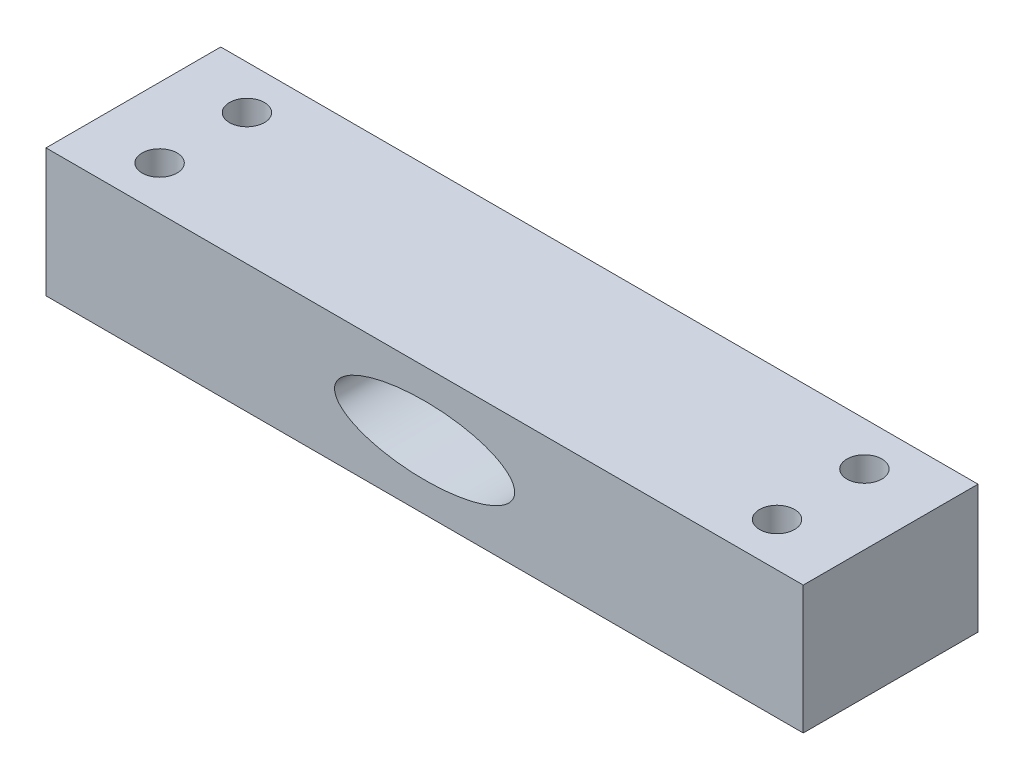
SolidWorks part; units mm, degrees
ref_plane "Front Plane" through (0, 0, 0) normal (0, 0, 1) x (1, 0, 0)
ref_plane "Top Plane" through (0, 0, 0) normal (0, 1, 0) x (1, 0, 0)
ref_plane "Right Plane" through (0, 0, 0) normal (1, 0, 0) x (0, 0, -1)
sketch "Sketch1" plane through (0, 0, 0) normal (0, 1, 0) x (1, 0, 0)
  line L1 (-65, -15) -> (65, -15)
  line L2 (-65, -15) -> (-65, 15)
  line L3 (-65, 15) -> (65, 15)
  line L4 (65, -15) -> (65, 15)
  line L5 (0, 15) -> (0, -15) construction
  line L6 (-65, 0) -> (65, 0) construction
  point P0 (0, 0)
  dimension "D1" = 130
  dimension "D2" = 30
extrude "Boss-Extrude1" add sketch "Sketch1" along normal blind 22
sketch "Sketch2" plane through (0, 0, 15) normal (0, 0, 1) x (1, 0, 0)
  ellipse E0 centre (0, 11) end of major axis (15.4617, 11) minor radius 5.8847
extrude "Cut-Extrude1" cut sketch "Sketch2" against normal through all
sketch "Sketch3" plane through (0, 22, 0) normal (0, 1, 0) x (1, 0, 0)
  line L0 (-1000, 0) -> (49000, 0) construction
  line L1 (0, -1000) -> (0, 49000) construction
  line L2 (-65, 15) -> (-65, -15) construction
  circle A0 centre (-53, 7.5) radius 3
  circle A1 centre (53, 7.5) radius 3
  circle A2 centre (53, -7.5) radius 3
  circle A3 centre (-53, -7.5) radius 3
  dimension "D1" = 6
  dimension "D2" = 12
  dimension "D3" = 7.5
extrude "Cut-Extrude2" cut sketch "Sketch3" against normal through all
sketch "Sketch4" plane through (-65, 0, 0) normal (-1, 0, 0) x (0, 0, 1)
  line L1 (-0.6925, 2.1211) -> (0.6925, 2.1211)
  line L2 (-0.6925, 2.1211) -> (-0.6925, 17.3245)
  line L3 (-0.6925, 17.3245) -> (0.6925, 17.3245)
  line L4 (0.6925, 2.1211) -> (0.6925, 17.3245)
  line L5 (0, 17.3245) -> (0, 2.1211) construction
  line L6 (-0.6925, 9.7228) -> (0.6925, 9.7228) construction
  point P0 (0, 9.7228)
extrude "Cut-Extrude3" cut sketch "Sketch4" against normal blind 2
